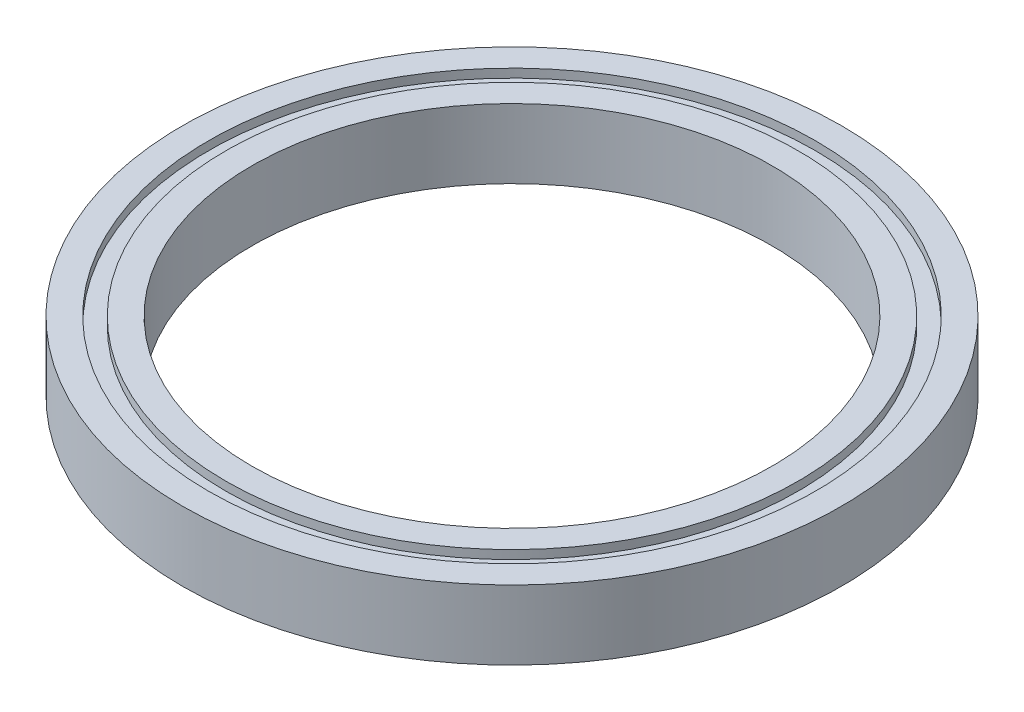
SolidWorks part; units mm, degrees
ref_plane "前视基准面" through (0, 0, 0) normal (0, 0, 1) x (1, 0, 0)
ref_plane "上视基准面" through (0, 0, 0) normal (0, 1, 0) x (1, 0, 0)
ref_plane "右视基准面" through (0, 0, 0) normal (1, 0, 0) x (0, 0, -1)
sketch "草图1" plane through (0, 0, 0) normal (0, 1, 0) x (1, 0, 0)
  circle A0 centre (0, 0) radius 38
  circle A1 centre (0, 0) radius 30
  dimension "D1" = 76
  dimension "D2" = 60
extrude "凸台-拉伸1" add sketch "草图1" along normal blind 8
sketch "草图2" plane through (0, 8, 0) normal (0, 1, 0) x (1, 0, 0)
  circle A0 centre (0, 0) radius 33 construction
  circle A1 centre (0, 0) radius 33
  circle A2 centre (0, 0) radius 35
  circle A3 centre (0, 0) radius 30 construction
  circle A4 centre (0, 0) radius 38 construction
  dimension "D1" = 3
  dimension "D2" = 3
extrude "切除-拉伸1" cut sketch "草图2" against normal blind 1
sketch "草图3" plane through (0, 0, 0) normal (0, -1, 0) x (1, 0, 0)
  circle A0 centre (0, 0) radius 33
  circle A1 centre (0, 0) radius 35
  circle A2 centre (0, 0) radius 30 construction
  circle A3 centre (0, 0) radius 38 construction
  dimension "D1" = 3
  dimension "D2" = 3
extrude "切除-拉伸2" cut sketch "草图3" against normal blind 1
